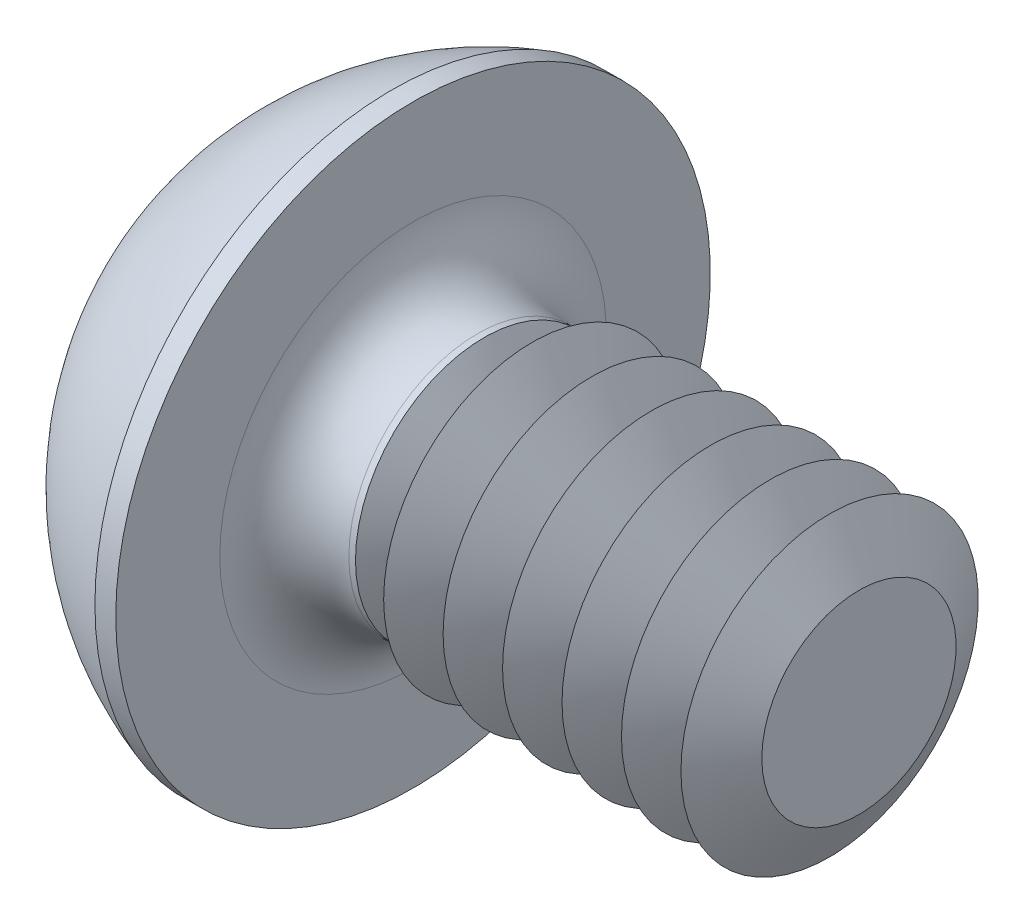
SolidWorks part; units mm, degrees
revolve "基体-旋转" add sketch "草图2" angle 360 about L0
sketch "草图2" plane through (0, 0, 0) normal (0, 0, 1) x (1, 0, 0)
  line L0 (-1.3318, 0) -> (6.5885, 0) construction
  line L1 (0, 0) -> (4.6, 0)
  line L2 (4.6, 0) -> (4.6, 1)
  line L3 (4.6, 1) -> (2.4, 1)
  line L4 (2.4, 1) -> (2.266, 0.866)
  line L5 (2.266, 0.866) -> (2.034, 0.866)
  line L6 (1.6, 1.3) -> (1.6, 2)
  line L7 (1.6, 2) -> (1.4597, 2)
  arc A0 (1.6, 1.3) -> (2.034, 0.866) centre (2.034, 1.3) ccw
  arc A1 (0, 0) -> (1.4597, 2) centre (2.1, 0) cw
  dimension "D3" = 2.1
  dimension "dk" = 4
  dimension "d" = 2
  dimension "l" = 3
  dimension "a" = 0.8
  dimension "D1" = 45
  dimension "D2" = 1.732
  dimension "da" = 2.6
  dimension "k" = 1.6
material "钢"
ref_plane "前视" through (0, 0, 0) normal (0, 0, 1) x (1, 0, 0)
ref_plane "上视" through (0, 0, 0) normal (0, 1, 0) x (1, 0, 0)
ref_plane "右视" through (0, 0, 0) normal (1, 0, 0) x (0, 0, -1)
sketch "尺寸草图" plane through (0, 0, 0) normal (0, 0, 1) x (1, 0, 0)
  line L0 (0, 0) -> (3, 0)
  line L1 (0, 0) -> (0, 4)
  line L2 (3, 0) -> (3, 2.6)
  point P5 (0, 2)
  point P6 (2.6, 0)
  point P7 (0.8, 0)
  point P8 (1.6, 0)
  point P9 (0.9, 0)
  point P10 (1.9, 0)
  point P11 (1.8, 0)
  dimension "dk" = 4
  dimension "d" = 2
  dimension "l" = 3
  dimension "a" = 0.8
  dimension "da" = 2.6
  dimension "k" = 1.6
  dimension "P" = 0.4
  dimension "rf" = 2.1
  dimension "m" = 1.9
  dimension "h" = 1.2
sketch "草图3" plane through (0, 0, 0) normal (0, 0, 1) x (1, 0, 0)
  line L0 (4.4022, 1) -> (4.8022, 1)
  line L1 (4.8022, 1) -> (4.6, 0.6536)
  line L2 (4.6, 0.6536) -> (4.4022, 1)
  line L3 (4.6, 1) -> (2.4, 1) construction
  line L4 (4.6, -1) -> (4.6, 1) construction
  line L5 (-0.2428, 0) -> (7.1644, 0) construction
  line L6 (-1.3318, 0) -> (6.5885, 0) construction
  dimension "P" = 0.4
  dimension "D1" = 0.3464
  dimension "D2" = 60
revolve "切除-旋转1" cut sketch "草图3" angle 360 about L5
sketch "草图5" plane through (0, 0, 0) normal (1, 0, 0) x (0, 0, -1)
  line L1 (0.2, 0.95) -> (-0.2, 0.95)
  line L2 (0.2, 0.95) -> (0.2, -0.95)
  line L3 (0.2, -0.95) -> (-0.2, -0.95)
  line L4 (-0.2, 0.95) -> (-0.2, -0.95)
  point P4 (0.2, 0)
  point P5 (0, 0.95)
  dimension "m" = 1.9
  dimension "D1" = 0.4
ref_plane "基准面1" through (1.2, 0, 0) normal (1, 0, 0) x (0, 0, -1)
pattern_linear "阵列(线性)1" count 7 spacing 0.4 along (-1, 0, 0) of "切除-旋转1"
sketch "草图6" plane through (1.2, 0, 0) normal (1, 0, 0) x (0, 0, -1)
  point P0 (0, 0)
loft "切除-放样1" cut profiles "草图6", "草图5"
ref_plane "基准面2" through (0, 0, 0) normal (0, -0.7071, 0.7071) x (1, 0, 0)
mirror "镜向1" about plane through (0, 0, 0) normal (0, -0.7071, 0.7071) of "切除-放样1"
equation "\"l@草图2\" = \"l@尺寸草图\""
equation "\"dk@草图2\" = \"dk@尺寸草图\""
equation "\"k@草图2\" = \"k@尺寸草图\""
equation "\"D2@草图2\" = \"d@尺寸草图\"*0.866"
equation "\"a@草图2\" = \"a@尺寸草图\""
equation "\"D3@草图2\" = \"rf@尺寸草图\""
equation "\"d@草图2\" = \"d@尺寸草图\""
equation "\"da@草图2\" = \"da@尺寸草图\""
equation "\"D2\"= \"d@尺寸草图\" * 0.866"
equation "\"D1\"= \"l@尺寸草图\" - \"a@尺寸草图\""
equation "\"P@草图3\" = \"P@尺寸草图\""
equation "\"D1@草图3\" = \"P@尺寸草图\"*0.866"
equation "\"h@基准面1\" = \"h@尺寸草图\""
equation "\"D1@草图5\" = \"P@尺寸草图\""
equation "\"m@草图5\" = \"m@尺寸草图\""
equation "\"D3@阵列(线性)1\" = \"P@尺寸草图\""
equation "\"D1@阵列(线性)1\" = (\"l@尺寸草图\"-\"a@尺寸草图\")/\"P@尺寸草图\"+1"
